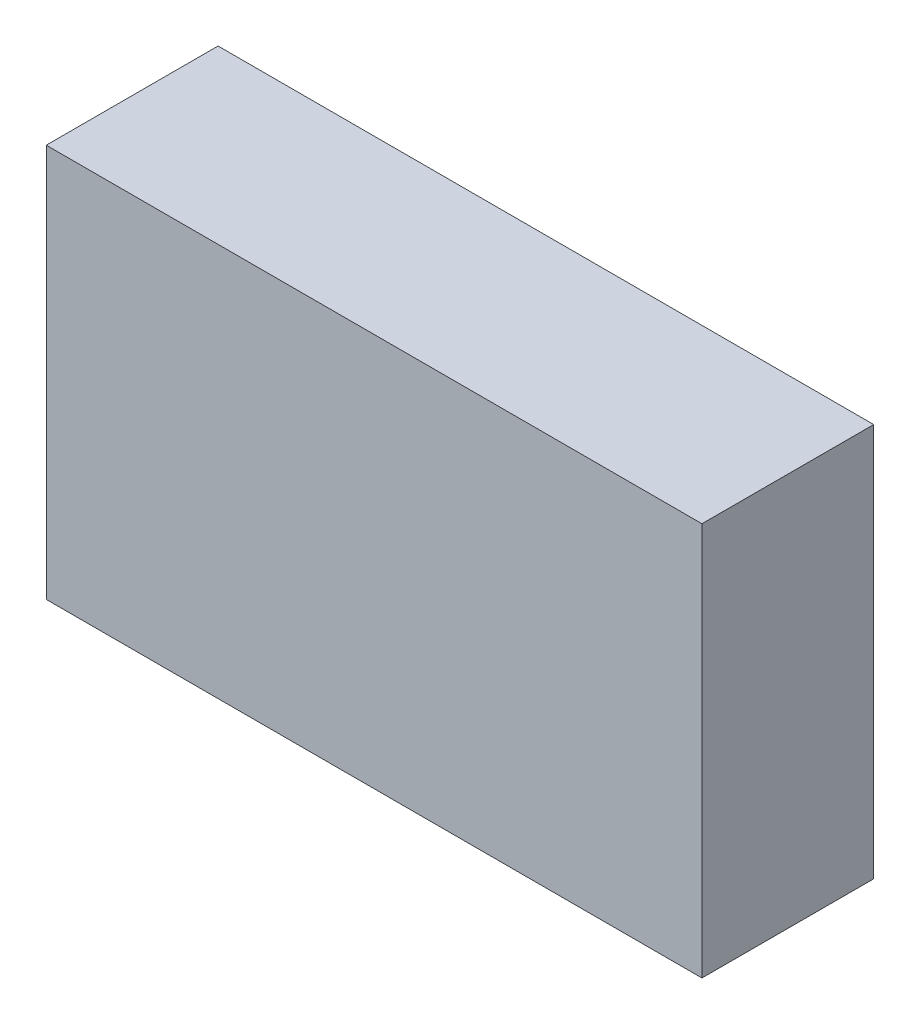
SolidWorks part; units mm, degrees
ref_plane "Front Plane" through (0, 0, 0) normal (0, 0, 1) x (1, 0, 0)
ref_plane "Top Plane" through (0, 0, 0) normal (0, 1, 0) x (1, 0, 0)
ref_plane "Right Plane" through (0, 0, 0) normal (1, 0, 0) x (0, 0, -1)
sketch "Sketch1" plane through (0, 0, 0) normal (0, 0, 1) x (1, 0, 0)
  line L1 (-75, 45) -> (75, 45)
  line L2 (-75, 45) -> (-75, -45)
  line L3 (-75, -45) -> (75, -45)
  line L4 (75, 45) -> (75, -45)
  line L5 (-75, 45) -> (75, -45) construction
  line L6 (-75, -45) -> (75, 45) construction
  point P0 (0, 0)
  dimension "D1" = 90
  dimension "D2" = 150
extrude "Boss-Extrude1" add sketch "Sketch1" along normal blind 39.3
